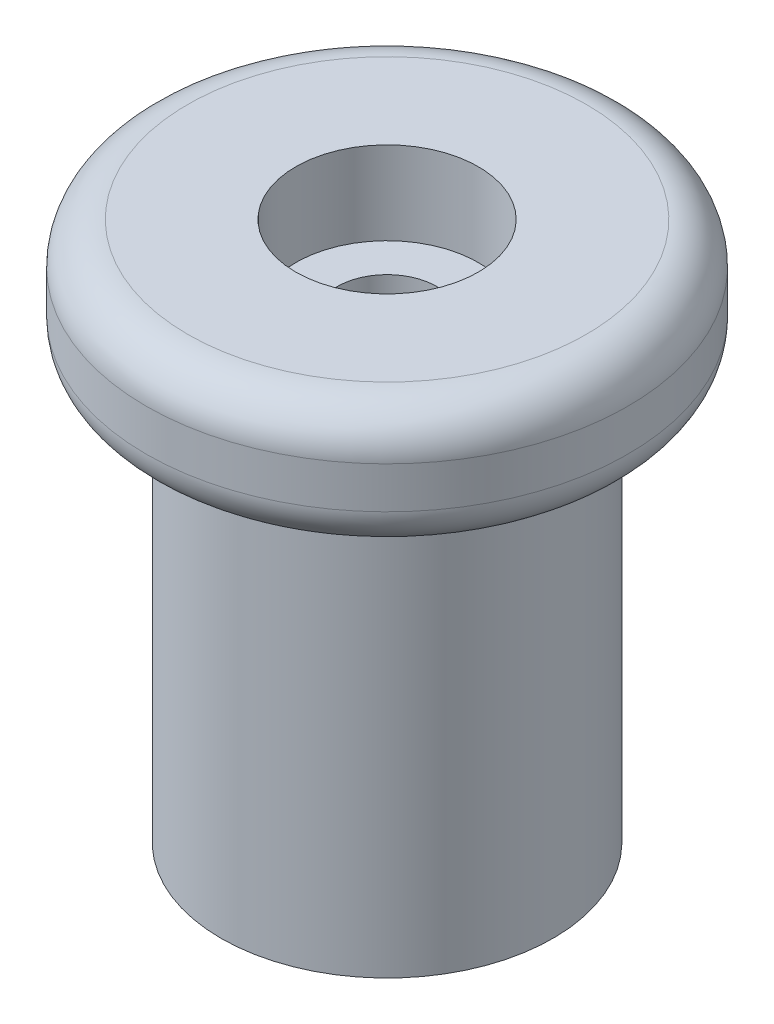
SolidWorks part; units mm, degrees
ref_plane "Front" through (0, 0, 0) normal (0, 0, 1) x (1, 0, 0)
ref_plane "Top" through (0, 0, 0) normal (0, 1, 0) x (1, 0, 0)
ref_plane "Right" through (0, 0, 0) normal (1, 0, 0) x (0, 0, -1)
sketch "草图1" plane through (0, 0, 0) normal (0, 1, 0) x (1, 0, 0)
  circle A0 centre (0, 0) radius 4
extrude "凸台-拉伸1" add sketch "草图1" along normal blind 10
sketch "草图2" plane through (0, 10, 0) normal (0, 1, 0) x (1, 0, 0)
  circle A0 centre (0, 0) radius 5.8
extrude "凸台-拉伸2" add sketch "草图2" along normal blind 3
sketch "草图3" plane through (0, 13, 0) normal (0, 1, 0) x (1, 0, 0)
  point P0 (0, 0)
hole_wizard "M2 凹头盖螺钉的柱形沉头孔1" positions "3D草图1" profile "草图4" counterbore size "M2" standard "ANSI Metric" end condition through all
sketch3d "3D草图1"
  point P0 (0, 0, 0)
  point P3 (0, 0, 0)
  point P6 (0, 13, 0)
sketch "草图4" plane through (0, 13, 0) normal (1, 0, 0) x (0, 0, 1)
  line L0 (0, 0) -> (0, 13)
  line L1 (0, 13) -> (1.2, 13)
  line L3 (1.2, 13) -> (1.2, 2)
  line L4 (1.2, 2) -> (2.2, 2)
  line L5 (2.2, 2) -> (2.2, 0)
  line L7 (2.2, 0) -> (0, 0)
  line L11 (0, -6.35) -> (0, 107.95) construction
  dimension "通孔孔直径" = 2.4
  dimension "通孔孔深度" = 13
  dimension "柱形沉头孔直径" = 4.4
  dimension "柱形沉头孔深度" = 2
fillet "圆角1" radius 1 2 edges at (0, 10, 5.8) (0, 13, 5.8)
